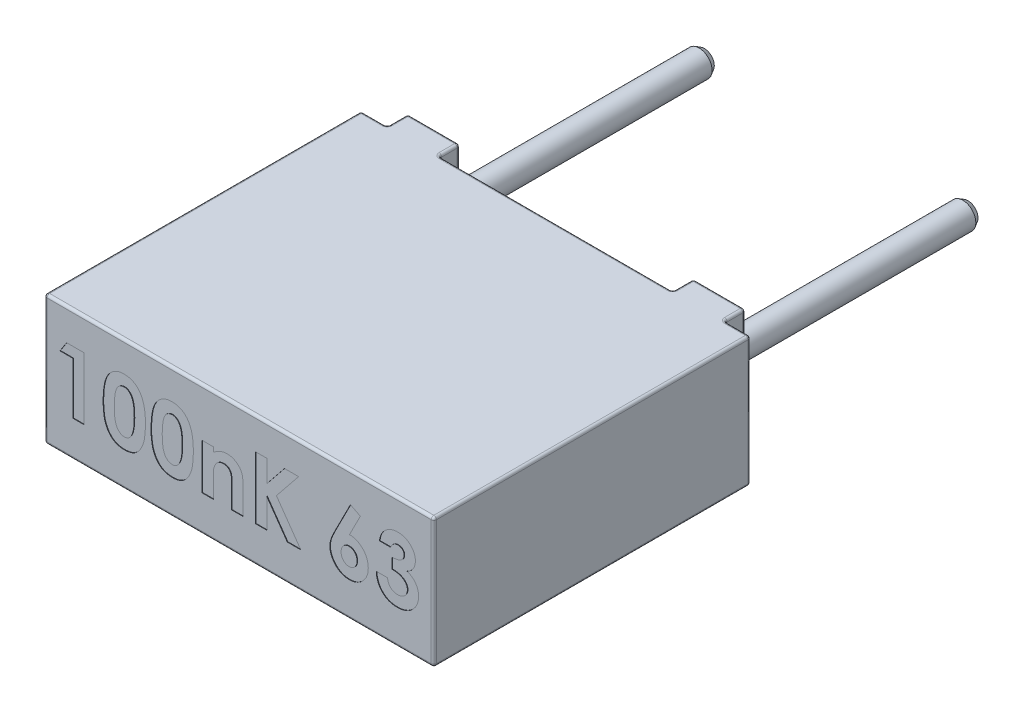
SolidWorks part; units mm, degrees
ref_plane "Alzado" through (0, 0, 0) normal (0, 0, 1) x (1, 0, 0)
ref_plane "Planta" through (0, 0, 0) normal (0, 1, 0) x (1, 0, 0)
ref_plane "Vista lateral" through (0, 0, 0) normal (1, 0, 0) x (0, 0, -1)
sketch "Croquis1" plane through (0, 0, 0) normal (0, 0, 1) x (1, 0, 0)
  line L1 (-3.75, 1.25) -> (3.75, 1.25)
  line L2 (-3.75, 1.25) -> (-3.75, -1.25)
  line L3 (-3.75, -1.25) -> (3.75, -1.25)
  line L4 (3.75, 1.25) -> (3.75, -1.25)
  line L5 (-3.75, 1.25) -> (3.75, -1.25) construction
  line L6 (-3.75, -1.25) -> (3.75, 1.25) construction
  point P0 (0, 0)
  dimension "D1" = 7.5
  dimension "D2" = 2.5
extrude "Saliente-Extruir1" add sketch "Croquis1" along normal blind 6.5
sketch "Croquis2" plane through (0, -1.25, 0) normal (0, -1, 0) x (1, 0, 0)
  line L0 (-4.2557, 0.4) -> (4.1804, 0.4) construction
  line L1 (-3.75, 0) -> (3.75, 0) construction
  line L2 (-3.25, -0.392) -> (-3.25, 1.1238) construction
  line L3 (0, -0.7592) -> (0, 1.9901) construction
  line L4 (-2.25, 1.1238) -> (-2.25, -0.5238) construction
  line L5 (-3.75, 6.5) -> (-3.75, 0) construction
  line L6 (-3.75, 0.4) -> (-3.25, 0.4)
  line L7 (-3.75, 0.4) -> (-3.75, 0)
  line L8 (-3.75, 0) -> (-3.25, 0)
  line L9 (-3.25, 0.4) -> (-3.25, 0)
  line L10 (2.25, 0) -> (-2.25, 0)
  line L11 (-2.25, 0) -> (-2.25, 0.4)
  line L12 (-2.25, 0.4) -> (2.25, 0.4)
  line L13 (2.25, 0) -> (2.25, 0.4)
  line L14 (3.25, 0.4) -> (3.25, 0)
  line L15 (3.75, 0) -> (3.25, 0)
  line L16 (3.75, 0.4) -> (3.75, 0)
  line L17 (3.75, 0.4) -> (3.25, 0.4)
  point P22 (0, 0.4)
  point P23 (0, 0)
  dimension "D1" = 0.4
  dimension "D2" = 3.25
  dimension "D3" = 2.25
extrude "Cortar-Extruir1" cut sketch "Croquis2" against normal through all
fillet "Redondeo1" radius 0.05 36 edges at (3.5, -1.25, 0.4) (2.25, -1.25, 0.2) (-3.25, -1.25, 0.2) (3.75, -1.25, 3.45) (-2.25, 0, 0.4) (3.25, 0, 0) (3.25, -1.25, 0.2) (2.75, -1.25, 0) (2.25, 0, 0.4) (0, -1.25, 0.4) (-2.25, -1.25, 0.2) (-2.75, -1.25, 0) (-3.5, -1.25, 0.4) (-3.25, 0, 0.4) (3.75, 0, 0.4) (3.25, 0, 0.4) (-3.75, 0, 0.4) (-3.5, 1.25, 0.4) (-3.25, 0, 0) (-3.25, 1.25, 0.2) (-2.75, 1.25, 0) (-2.25, 1.25, 0.2) (-2.25, 0, 0) (0, 1.25, 0.4) (2.25, 0, 0) (2.25, 1.25, 0.2) (2.75, 1.25, 0) (3.25, 1.25, 0.2) (3.5, 1.25, 0.4) (-3.75, -1.25, 3.45) (-3.75, 1.25, 3.45) (3.75, 1.25, 3.45) (3.75, 0, 6.5) (0, -1.25, 6.5) (-3.75, 0, 6.5) (0, 1.25, 6.5)
sketch "Croquis3" plane through (0, 0, 0) normal (0, 0, -1) x (-1, 0, 0)
  line L0 (4.1577, 0) -> (-4.4433, 0) construction
  circle A0 centre (-2.54, 0) radius 0.25
  circle A1 centre (2.54, 0) radius 0.25
  point P9 (0, 0)
  dimension "D1" = 0.5
  dimension "D2" = 0.5
  dimension "D3" = 2.54
  dimension "D4" = 2.54
extrude "Saliente-Extruir2" add sketch "Croquis3" along normal blind 5 separate body
chamfer "Chaflán1" distance 0.1 angle 30 1 edges at (2.29, 0, -5)
chamfer "Chaflán2" distance 0.1 angle 30 1 edges at (-2.79, 0, -5)
sketch "Croquis4" plane through (0, 0, 6.5) normal (0, 0, 1) x (1, 0, 0)
  text T0 "<b>100nK 63</b>" font "Century Gothic" height 1.2
extrude "Cortar-Extruir2" cut sketch "Croquis4" against normal blind 0.01
